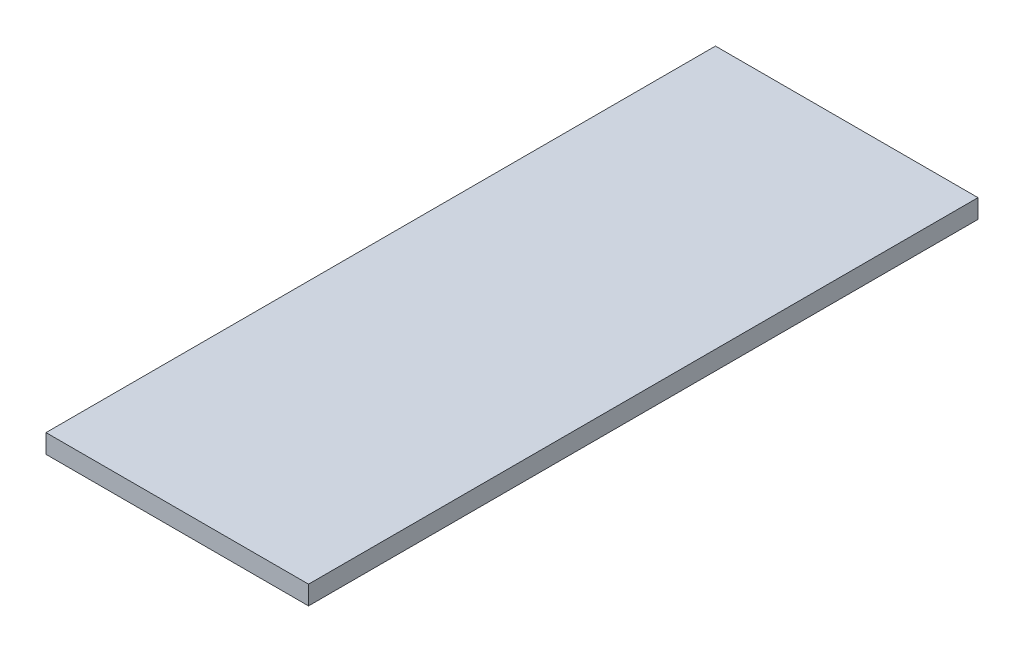
SolidWorks part; units mm, degrees
material "Pine"
ref_plane "Front Plane" through (0, 0, 0) normal (0, 0, 1) x (1, 0, 0)
ref_plane "Top Plane" through (0, 0, 0) normal (0, 1, 0) x (1, 0, 0)
ref_plane "Right Plane" through (0, 0, 0) normal (1, 0, 0) x (0, 0, -1)
sketch "Sketch1" plane through (0, 0, 0) normal (0, 1, 0) x (1, 0, 0)
  line L1 (127, -209.55) -> (-127, -209.55)
  line L2 (127, -209.55) -> (127, 438.15)
  line L3 (127, 438.15) -> (-127, 438.15)
  line L4 (-127, -209.55) -> (-127, 438.15)
  point P0 (0, 0)
  point P4 (0, -209.55)
  dimension "D1" = 254
  dimension "D2" = 438.15
  dimension "D3" = 647.7
extrude "Boss-Extrude1" add sketch "Sketch1" along normal blind 18.2562
